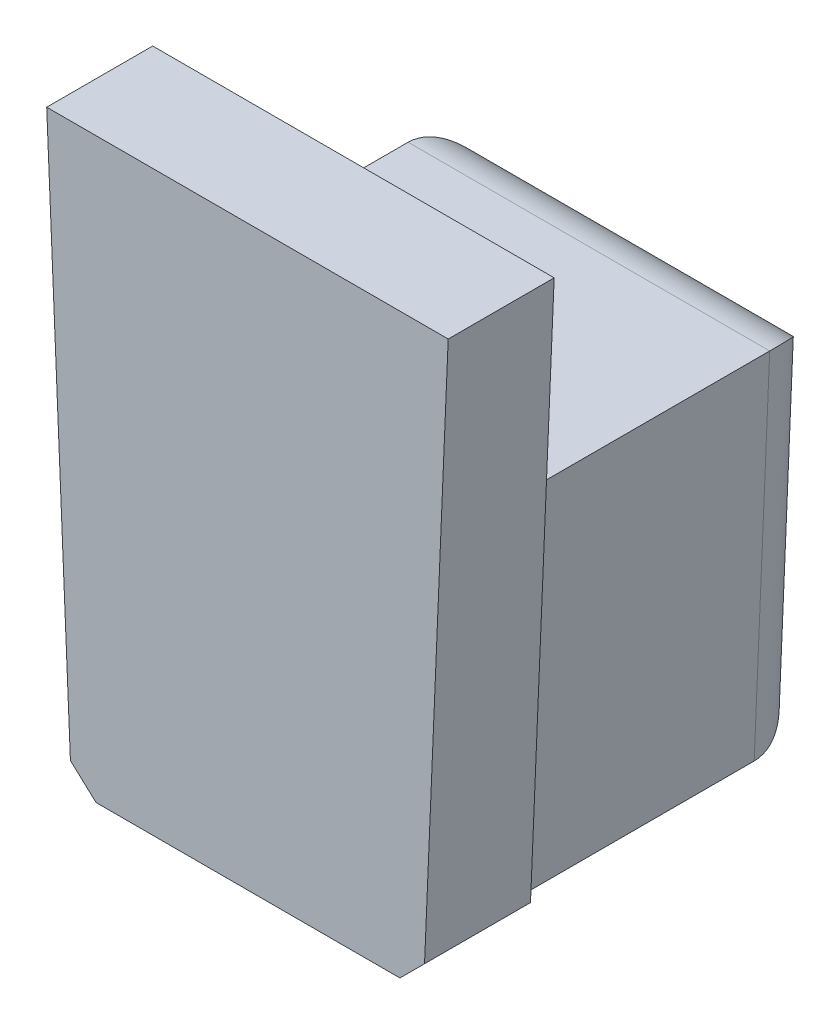
SolidWorks part; units mm, degrees
ref_plane "Front" through (0, 0, 0) normal (0, 0, 1) x (1, 0, 0)
ref_plane "Top" through (0, 0, 0) normal (0, 1, 0) x (1, 0, 0)
ref_plane "Right" through (0, 0, 0) normal (1, 0, 0) x (0, 0, -1)
sketch "Sketch1" plane through (0, 0, 0) normal (0, 0, 1) x (1, 0, 0)
  line L0 (0, 0) -> (68.2, 0)
  line L1 (68.2, 0) -> (64, -98.1)
  line L2 (64, -98.1) -> (4.2, -98.1)
  line L3 (4.2, -98.1) -> (0, 0)
  line L4 (68.2, 0) -> (68.2, -98.1) construction
  line L5 (68.2, -98.1) -> (64, -98.1) construction
  line L6 (0, 0) -> (0, -98.1) construction
  line L7 (0, -98.1) -> (4.2, -98.1) construction
  dimension "D1" = 68.2
  dimension "D2" = 59.8
  dimension "D3" = 98.1
extrude "Boss-Extrude1" add sketch "Sketch1" along normal blind 18
sketch "Sketch2" plane through (0, 0, 0) normal (0, 0, -1) x (-1, 0, 0)
  line L0 (-62.1694, -94.1) -> (-6.0306, -94.1)
  line L1 (-6.0306, -94.1) -> (-3.3914, -32.4561)
  line L2 (-3.3914, -32.4561) -> (-64.8086, -32.4561)
  line L3 (-64.8086, -32.4561) -> (-62.1694, -94.1)
  line L4 (-4.2, -98.1) -> (-64, -98.1) construction
  line L5 (0, 0) -> (-4.2, -98.1) construction
  line L6 (-64, -98.1) -> (-68.2, 0) construction
  dimension "D1" = 4
  dimension "D2" = 2
  dimension "D3" = 2
  dimension "D4" = 2
  dimension "D5" = 2
extrude "Boss-Extrude2" add sketch "Sketch2" along normal blind 50
chamfer "Chamfer1" distance 4 angle 45 2 edges at (64, -98.1, 9) (4.2, -98.1, 9)
fillet "Fillet1" radius 10 4 edges at (63.489, -63.2781, -50) (4.711, -63.2781, -50) (34.1, -94.1, -50) (34.1, -32.4561, -50)
